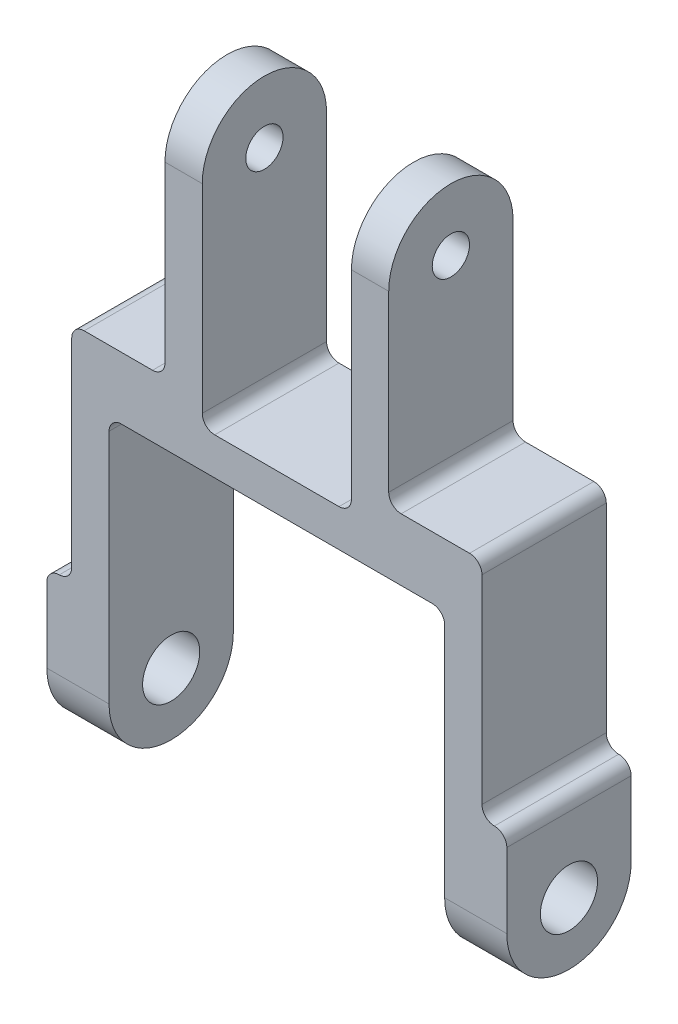
SolidWorks part; units mm, degrees
material "ABS"
ref_plane "Plan de face" through (0, 0, 0) normal (0, 0, 1) x (1, 0, 0)
ref_plane "Plan de dessus" through (0, 0, 0) normal (0, 1, 0) x (1, 0, 0)
ref_plane "Plan de droite" through (0, 0, 0) normal (1, 0, 0) x (0, 0, -1)
sketch "Esquisse1" plane through (0, 0, 0) normal (0, 0, 1) x (1, 0, 0)
  line L0 (-17.2403, -13.1007) -> (-17.2403, -2.1007)
  line L1 (-17.2403, -13.1007) -> (-12.2403, -13.1007)
  line L2 (-12.2403, -13.1007) -> (-12.2403, 10.8993)
  line L3 (-11.2403, 11.8993) -> (13.7597, 11.8993)
  line L4 (7.2597, 36.8993) -> (7.2597, 15.8993)
  line L5 (10.2597, 36.8993) -> (7.2597, 36.8993)
  line L6 (10.2597, 17.8993) -> (10.2597, 36.8993)
  line L8 (-15.2403, -0.1007) -> (-15.2403, 15.8993)
  line L9 (-14.2403, 16.8993) -> (-8.7403, 16.8993)
  line L10 (-7.7403, 17.8993) -> (-7.7403, 36.8993)
  line L11 (-7.7403, 36.8993) -> (-4.7403, 36.8993)
  line L12 (-4.7403, 36.8993) -> (-4.7403, 15.8993)
  line L13 (-3.7403, 14.8993) -> (6.2597, 14.8993)
  line L14 (16.7597, 16.8993) -> (11.2597, 16.8993)
  line L15 (1.2597, 4.2535) -> (1.2597, 14.8993) construction
  line L16 (17.7597, -0.1007) -> (17.7597, 15.8993)
  line L18 (14.7597, -13.1007) -> (14.7597, 10.8993)
  line L19 (19.7597, -13.1007) -> (14.7597, -13.1007)
  line L20 (19.7597, -13.1007) -> (19.7597, -2.1007)
  arc A0 (-17.2403, -2.1007) -> (-16.2403, -1.1007) centre (-16.2403, -2.1007) cw
  arc A1 (-16.2403, -1.1007) -> (-15.2403, -0.1007) centre (-16.2403, -0.1007) ccw
  arc A2 (-4.7403, 15.8993) -> (-3.7403, 14.8993) centre (-3.7403, 15.8993) ccw
  arc A3 (-15.2403, 15.8993) -> (-14.2403, 16.8993) centre (-14.2403, 15.8993) cw
  arc A4 (-8.7403, 16.8993) -> (-7.7403, 17.8993) centre (-8.7403, 17.8993) ccw
  arc A5 (-12.2403, 10.8993) -> (-11.2403, 11.8993) centre (-11.2403, 10.8993) cw
  arc A6 (14.7597, 10.8993) -> (13.7597, 11.8993) centre (13.7597, 10.8993) ccw
  arc A7 (11.2597, 16.8993) -> (10.2597, 17.8993) centre (11.2597, 17.8993) cw
  arc A8 (17.7597, 15.8993) -> (16.7597, 16.8993) centre (16.7597, 15.8993) ccw
  arc A9 (7.2597, 15.8993) -> (6.2597, 14.8993) centre (6.2597, 15.8993) cw
  arc A10 (18.7597, -1.1007) -> (17.7597, -0.1007) centre (18.7597, -0.1007) cw
  arc A11 (19.7597, -2.1007) -> (18.7597, -1.1007) centre (18.7597, -2.1007) ccw
  point P0 (0, 0)
  point P47 (1.2597, 11.8993)
  dimension "D2" = 1
  dimension "D1" = 1
  dimension "D3" = 3
  dimension "D4" = 3
  dimension "D5" = 3
  dimension "D6" = 5
  dimension "D7" = 50
  dimension "D8" = 6
  dimension "D9" = 5
  dimension "D10" = 13.5
  dimension "D11" = 20
extrude "Boss.-Extru.1" add sketch "Esquisse1" along normal blind 10
sketch "Esquisse2" plane through (-17.2403, 0, 0) normal (-1, 0, 0) x (0, 0, 1)
  line L2 (0, -8.1007) -> (0, -13.1007)
  line L3 (0, -13.1007) -> (10, -13.1007)
  line L4 (10, -13.1007) -> (10, -8.1007)
  line L5 (10, 36.8993) -> (10, 17.8993) construction
  line L6 (0, 36.8993) -> (0, 17.8993) construction
  line L8 (0, 31.8993) -> (0, 36.8993)
  line L9 (0, 36.8993) -> (10, 36.8993)
  line L10 (10, 36.8993) -> (10, 31.8993)
  line L11 (10, -2.1007) -> (10, -13.1007) construction
  arc A0 (10, -8.1007) -> (0, -8.1007) centre (5, -8.1007) cw
  arc A1 (10, 31.8993) -> (0, 31.8993) centre (5, 31.8993) ccw
  circle A2 centre (5, 31.8993) radius 1.5
  circle A3 centre (5, -8.1007) radius 2.3
  point P14 (5, 36.8993)
  line M3 (0, -2.1007) -> (0, -13.1007)
  line M4 (0, -13.1007) -> (10, -13.1007)
  line M5 (10, -13.1007) -> (10, -2.1007)
  dimension "D1" = 4.6
  dimension "D2" = 3
extrude "Enlèv. mat.-Extru.1" cut sketch "Esquisse2" against normal through all contours A1 L9 L8 | A1 L10 L9 | A0 L3 M5 | A0 M4 M3 | A2 | A3
